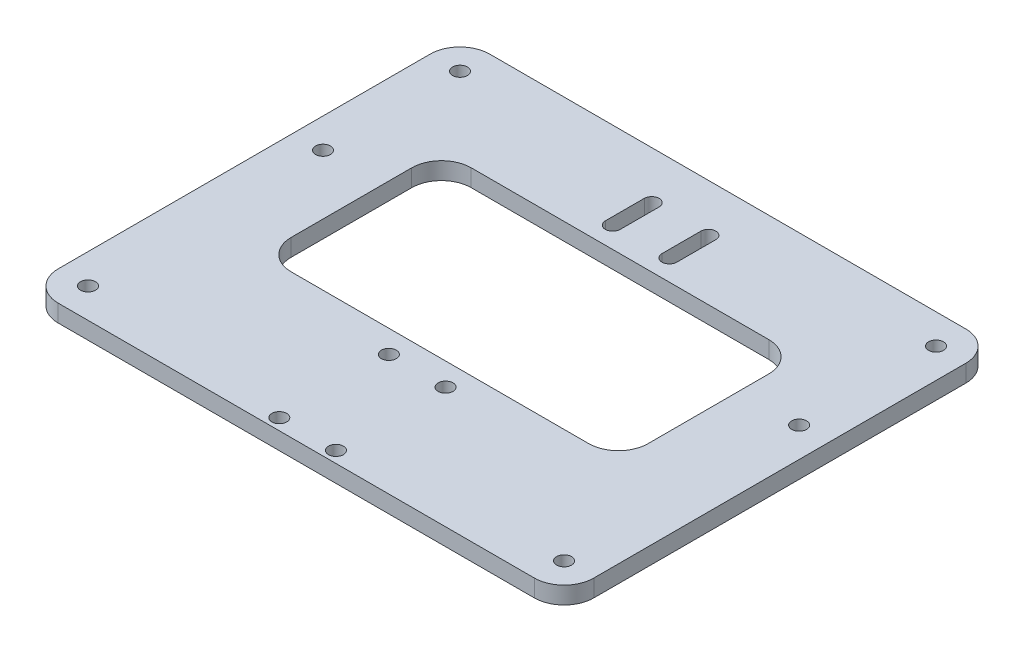
SolidWorks part; units mm, degrees
material "Acrylic (Medium-high impact)"
ref_plane "Front Plane" through (0, 0, 0) normal (0, 0, 1) x (1, 0, 0)
ref_plane "Top Plane" through (0, 0, 0) normal (0, 1, 0) x (1, 0, 0)
ref_plane "Right Plane" through (0, 0, 0) normal (1, 0, 0) x (0, 0, -1)
sketch "Sketch1" plane through (0, 0, 0) normal (0, 1, 0) x (1, 0, 0)
  line L1 (-90, -85) -> (90, -85)
  line L2 (-90, -85) -> (-90, 60)
  line L3 (-90, 60) -> (90, 60)
  line L4 (90, -85) -> (90, 60)
  point P0 (0, 0)
  dimension "D1" = 180
  dimension "D2" = 85
  dimension "D3" = 145
extrude "Boss-Extrude1" add sketch "Sketch1" along normal mid plane 5.8
sketch "Sketch2" plane through (0, 2.9, 0) normal (0, 1, 0) x (1, 0, 0)
  line L0 (90, 60) -> (-90, 60) construction
  line L1 (-60, 23.8) -> (60, 23.8)
  line L2 (-60, 23.8) -> (-60, -23.8)
  line L4 (60, 23.8) -> (60, -23.8)
  line L5 (-90, -85) -> (90, -85) construction
  line L8 (-60, -23.8) -> (-60, -36.74)
  line L9 (-60, -36.74) -> (60, -36.74)
  line L10 (60, -23.8) -> (60, -36.74)
  point P9 (0, 60)
  point P12 (0, -85)
  point P13 (-60, 0)
  point P14 (60, 0)
  dimension "D1" = 60.54
  dimension "D2" = 120
  dimension "D4" = 48.26
extrude "Cut-Extrude1" cut sketch "Sketch2" against normal through all
sketch "Sketch3" plane through (0, 2.9, 0) normal (0, 1, 0) x (1, 0, 0)
  line L0 (-9.525, 30.8897) -> (-9.525, 43.9821) construction
  line L1 (-12.025, 30.8897) -> (-12.025, 43.9821)
  line L2 (-7.025, 30.8897) -> (-7.025, 43.9821)
  line L3 (9.525, 30.8897) -> (9.525, 43.9821) construction
  line L4 (7.025, 30.8897) -> (7.025, 43.9821)
  line L5 (12.025, 30.8897) -> (12.025, 43.9821)
  line L6 (60, 23.8) -> (-60, 23.8) construction
  line L8 (-9.525, -44.36) -> (9.525, -44.36) construction
  line L10 (-9.525, 43.9821) -> (9.525, 43.9821) construction
  arc A0 (-12.025, 30.8897) -> (-7.025, 30.8897) centre (-9.525, 30.8897) ccw
  arc A1 (-7.025, 43.9821) -> (-12.025, 43.9821) centre (-9.525, 43.9821) ccw
  arc A2 (7.025, 30.8897) -> (12.025, 30.8897) centre (9.525, 30.8897) ccw
  arc A3 (12.025, 43.9821) -> (7.025, 43.9821) centre (9.525, 43.9821) ccw
  circle A4 centre (-9.525, -44.36) radius 2.5
  circle A5 centre (9.525, -44.36) radius 2.5
  circle A6 centre (-9.525, -81.19) radius 2.5
  circle A7 centre (9.525, -81.19) radius 2.5
  circle A8 centre (-9.525, -44.36) radius 2.54 construction
  circle A9 centre (-9.525, -81.19) radius 2.5 construction
  point P3 (-9.525, 37.4359)
  point P10 (9.525, 37.4359)
  point P27 (0, -44.36)
  point P32 (0, 43.9821)
  dimension "D5" = 5
  dimension "D1" = 5
  dimension "D2" = 13.0924
  dimension "D3" = 13.6359
extrude "Cut-Extrude2" cut sketch "Sketch3" against normal through all
sketch "Sketch4" plane through (0, 2.9, 0) normal (0, 1, 0) x (1, 0, 0)
  line L0 (-90, -85) -> (90, -85) construction
  line L1 (90, 60) -> (-90, 60) construction
  line L2 (-90, 60) -> (-90, -85) construction
  line L3 (90, -85) -> (90, 60) construction
  circle A0 centre (-80, 50) radius 2.5
  circle A1 centre (-80, 3.9983) radius 2.5
  circle A2 centre (-80, -75) radius 2.5
  circle A3 centre (80, -75) radius 2.5
  circle A4 centre (80, 3.9983) radius 2.5
  circle A5 centre (80, 50) radius 2.5
  dimension "D5" = 5
  dimension "D1" = 10
  dimension "D2" = 10
  dimension "D3" = 10
  dimension "D4" = 10
extrude "Cut-Extrude3" cut sketch "Sketch4" against normal through all
fillet "Fillet1" radius 10 8 edges at (90, 0, 85) (-90, 0, 85) (90, 0, -60) (-90, 0, -60) (-60, 0, -23.8) (60, 0, -23.8) (-60, 0, 36.74) (60, 0, 36.74)
